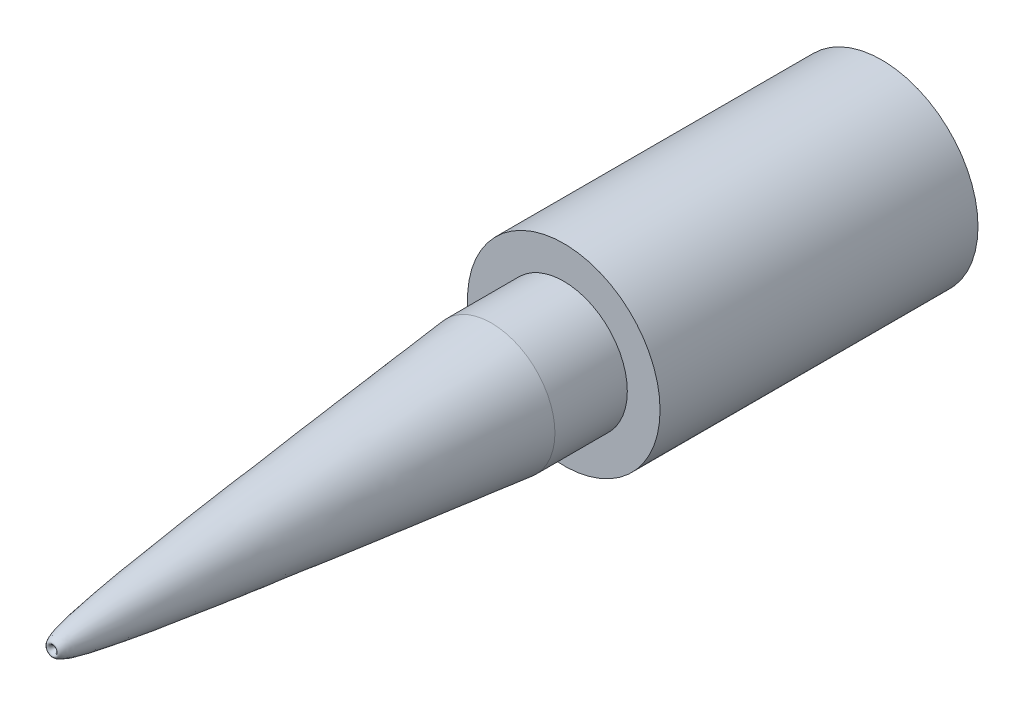
SolidWorks part; units mm, degrees
ref_plane "Alzado" through (0, 0, 0) normal (0, 0, 1) x (1, 0, 0)
ref_plane "Planta" through (0, 0, 0) normal (0, 1, 0) x (1, 0, 0)
ref_plane "Vista lateral" through (0, 0, 0) normal (1, 0, 0) x (0, 0, -1)
sketch "Sketch1" plane through (0, 0, 0) normal (0, 0, 1) x (1, 0, 0)
  circle A0 centre (0, 0) radius 9.6
  dimension "D1" = 19.2
extrude "Boss-Extrude1" add sketch "Sketch1" along normal blind 31.71
sketch "Sketch4" plane through (0, 0, 0) normal (0, 0, -1) x (-1, 0, 0)
  circle A0 centre (0, 0) radius 8.42
  dimension "D1" = 16.84
extrude "Cut-Extrude1" cut sketch "Sketch4" against normal blind 3.01
sketch "Sketch5" plane through (0, 0, 3.01) normal (0, 0, -1) x (-1, 0, 0)
  circle A0 centre (0, 0) radius 2
  circle A1 centre (0, 0) radius 7.185
  dimension "D1" = 4
  dimension "D2" = 14.37
extrude "Cut-Extrude3" cut sketch "Sketch5" against normal blind 12.61 contours A1
sketch "Sketch6" plane through (0, 0, 15.62) normal (0, 0, -1) x (-1, 0, 0)
  circle A0 centre (0, 0) radius 2
  dimension "D1" = 4
extrude "Boss-Extrude2" add sketch "Sketch6" along normal blind 9.58
chamfer "Chamfer1" distance 1.33 angle 45 1 edges at (-2, 0, 6.04)
sketch "Sketch7" plane through (0, 0, 31.71) normal (0, 0, 1) x (1, 0, 0)
  circle A0 centre (0, 0) radius 6.335
  dimension "D1" = 12.67
extrude "Boss-Extrude3" add sketch "Sketch7" along normal blind 7.22
sketch "Sketch10" plane through (0, 0, 0) normal (1, 0, 0) x (0, 0, -1)
  line L0 (-81.78, 0) -> (-38.93, 0)
  line L1 (-38.93, 6.335) -> (-38.93, -6.335) construction
  line L2 (-38.93, 0) -> (-38.93, 6.335)
  line L3 (-81.78, 0) -> (-38.93, 0) construction
  conic Q0 (-38.93, 6.335) -> (-81.78, 0) control (-86.4413, 1.361) rho 0.635738
  point P3 (0, 0)
  point P10 (-86.0769, 0)
  point P11 (-86.4413, 1.361)
  dimension "D1" = 42.85
revolve "Revolve2" add sketch "Sketch10" angle 360 about L3
